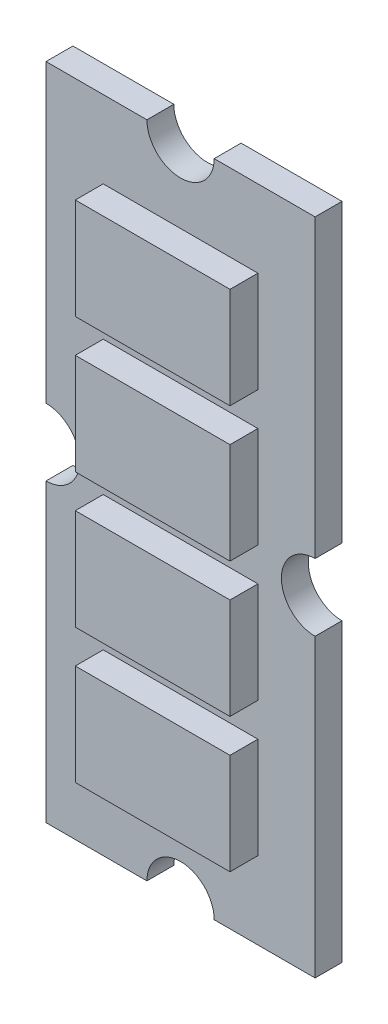
SolidWorks part; units mm, degrees
ref_plane "Front Plane" through (0, 0, 0) normal (0, 0, 1) x (1, 0, 0)
ref_plane "Top Plane" through (0, 0, 0) normal (0, 1, 0) x (1, 0, 0)
ref_plane "Right Plane" through (0, 0, 0) normal (1, 0, 0) x (0, 0, -1)
sketch "Sketch1" plane through (0, 0, 0) normal (0, 0, 1) x (1, 0, 0)
  line L0 (1.1976, -16.8459) -> (4.1976, -16.8459)
  line L1 (-3.8024, -16.8459) -> (-0.8024, -16.8459)
  line L2 (-3.8024, -16.8459) -> (-3.8024, -25.6459)
  line L3 (-3.8024, -36.4459) -> (-0.8024, -36.4459)
  line L4 (4.1976, -16.8459) -> (4.1976, -25.6459)
  line L5 (4.1976, -27.6459) -> (4.1976, -36.4459)
  line L6 (-3.8024, -27.6459) -> (-3.8024, -36.4459)
  line L7 (1.1976, -36.4459) -> (4.1976, -36.4459)
  arc A0 (-0.8024, -16.8459) -> (1.1976, -16.8459) centre (0.1976, -16.8459) ccw
  arc A1 (1.1976, -36.4459) -> (-0.8024, -36.4459) centre (0.1976, -36.4459) ccw
  arc A2 (4.1976, -25.6459) -> (4.1976, -27.6459) centre (4.1976, -26.6459) ccw
  arc A3 (-3.8024, -27.6459) -> (-3.8024, -25.6459) centre (-3.8024, -26.6459) ccw
  point P12 (0.1976, -16.8459)
  point P13 (4.1976, -26.6459)
  point P14 (-3.8024, -26.6459)
  point P15 (0.1976, -36.4459)
  dimension "D3" = 2
  dimension "D1" = 19.6
  dimension "D2" = 8
extrude "Extrude1" add sketch "Sketch1" along normal blind 0.8
sketch "Sketch2" plane through (0, 0, 0.8) normal (0, 0, 1) x (1, 0, 0)
  line L0 (4.1976, -25.6459) -> (4.1976, -16.8459) construction
  line L1 (-2.1024, -19.1459) -> (2.4976, -19.1459)
  line L2 (-2.1024, -19.1459) -> (-2.1024, -22.1459)
  line L3 (-2.1024, -34.1459) -> (2.4976, -34.1459)
  line L4 (2.4976, -19.1459) -> (2.4976, -22.1459)
  line L5 (-2.1024, -22.1459) -> (2.4976, -22.1459)
  line L7 (-2.1024, -23.1459) -> (2.4976, -23.1459)
  line L9 (-2.1024, -26.1459) -> (2.4976, -26.1459)
  line L11 (-2.1024, -27.1459) -> (2.4976, -27.1459)
  line L13 (-2.1024, -30.1459) -> (2.4976, -30.1459)
  line L15 (-2.1024, -31.1459) -> (2.4976, -31.1459)
  line L17 (-3.8024, -16.8459) -> (-3.8024, -25.6459) construction
  line L18 (4.1976, -16.8459) -> (1.1976, -16.8459) construction
  line L19 (1.1976, -36.4459) -> (4.1976, -36.4459) construction
  line L20 (-2.1024, -23.1459) -> (-2.1024, -26.1459)
  line L21 (2.4976, -23.1459) -> (2.4976, -26.1459)
  line L22 (2.4976, -27.1459) -> (2.4976, -30.1459)
  line L23 (-2.1024, -27.1459) -> (-2.1024, -30.1459)
  line L24 (-2.1024, -31.1459) -> (-2.1024, -34.1459)
  line L25 (2.4976, -31.1459) -> (2.4976, -34.1459)
  dimension "D1" = 1.7
  dimension "D2" = 1.7
  dimension "D3" = 2.3
  dimension "D4" = 2.3
  dimension "D5" = 3
  dimension "D6" = 3
  dimension "D7" = 3
  dimension "D8" = 3
  dimension "D9" = 1
  dimension "D10" = 1
extrude "Extrude2" add sketch "Sketch2" along normal blind 0.83
